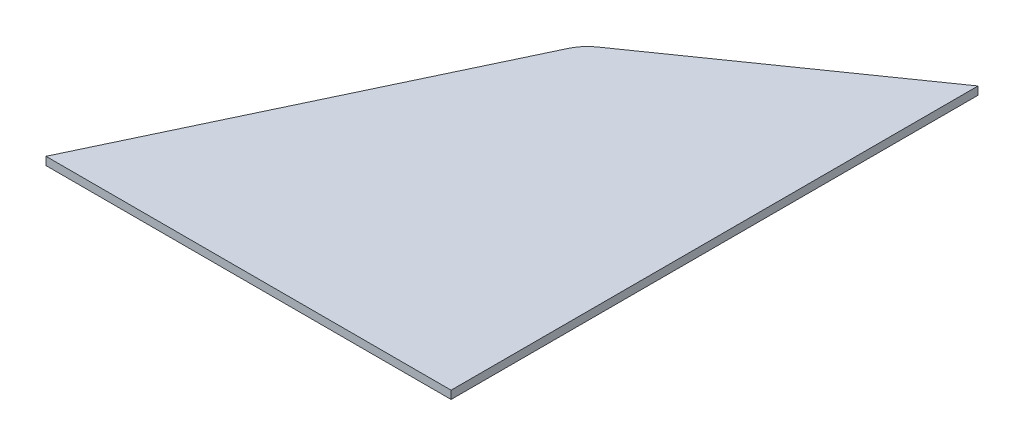
SolidWorks part; units mm, degrees
material "Plástico personalizado"
ref_plane "Plano frontal" through (0, 0, 0) normal (0, 0, 1) x (1, 0, 0)
ref_plane "Plano superior" through (0, 0, 0) normal (0, 1, 0) x (1, 0, 0)
ref_plane "Plano direito" through (0, 0, 0) normal (1, 0, 0) x (0, 0, -1)
sketch "Esboço1" plane through (0, 0, 0) normal (0, 1, 0) x (1, 0, 0)
  line L0 (0, 0) -> (100.1, 0)
  line L1 (100.1, 0) -> (100.1, 130.2)
  line L2 (100.1, 130.2) -> (42.5645, 90)
  line L3 (42.5645, 90) -> (0, 0)
  dimension "D1" = 100.1
  dimension "D2" = 130.2
  dimension "D3" = 90
  dimension "D4" = 90
extrude "Ressalto-extrusão1" add sketch "Esboço1" along normal blind 2
fillet "Filete1" radius 10 1 edges at (42.5645, 1, -90)
